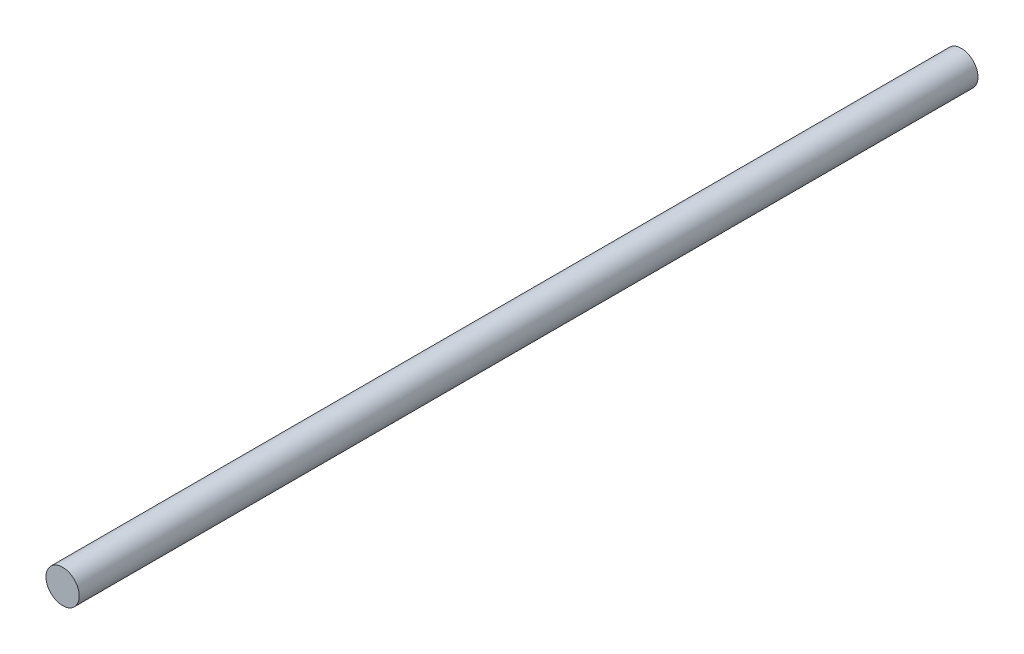
SolidWorks part; units mm, degrees
ref_plane "Front Plane" through (0, 0, 0) normal (0, 0, 1) x (1, 0, 0)
ref_plane "Top Plane" through (0, 0, 0) normal (0, 1, 0) x (1, 0, 0)
ref_plane "Right Plane" through (0, 0, 0) normal (1, 0, 0) x (0, 0, -1)
sketch "Sketch1" plane through (0, 0, 0) normal (0, 0, 1) x (1, 0, 0)
  circle A0 centre (0, 0) radius 2.5
  dimension "D1" = 5
extrude "Boss-Extrude1" add sketch "Sketch1" along normal blind 135
